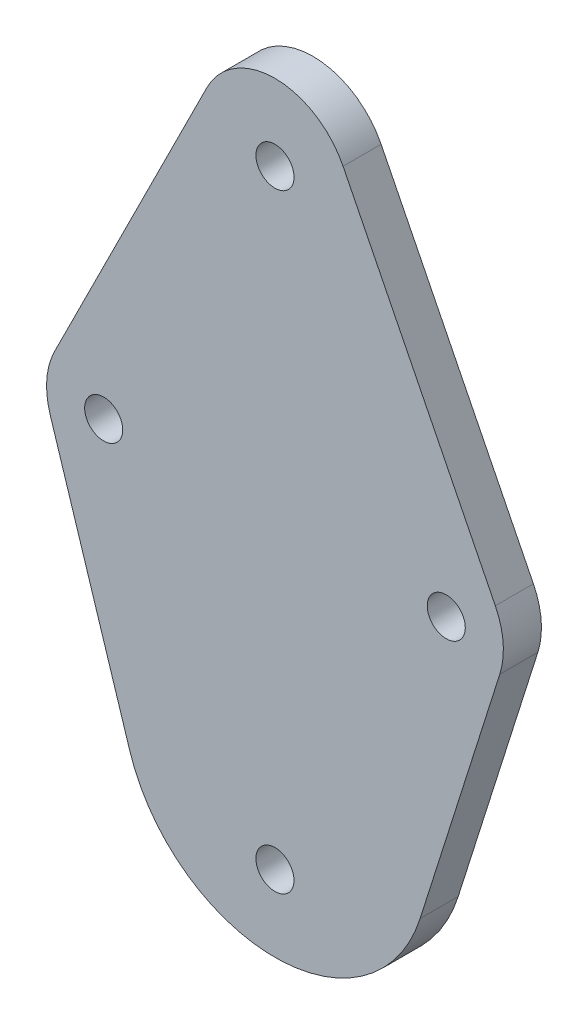
SolidWorks part; units mm, degrees
ref_plane "Front Plane" through (0, 0, 0) normal (0, 0, 1) x (1, 0, 0)
ref_plane "Top Plane" through (0, 0, 0) normal (0, 1, 0) x (1, 0, 0)
ref_plane "Right Plane" through (0, 0, 0) normal (1, 0, 0) x (0, 0, -1)
sketch "Sketch1" plane through (0, 0, 0) normal (0, 0, 1) x (1, 0, 0)
  line L0 (28.9443, 4.4721) -> (8.9443, 44.4721)
  line L1 (-8.9443, 44.4721) -> (-28.9443, 4.4721)
  line L2 (-29.5325, -3.0217) -> (-19.0651, -36.0434)
  line L3 (19.0651, -36.0434) -> (29.5325, -3.0217)
  arc A0 (8.9443, 44.4721) -> (-8.9443, 44.4721) centre (0, 40) ccw
  arc A1 (-19.0651, -36.0434) -> (19.0651, -36.0434) centre (0, -30) ccw
  arc A2 (28.9443, 4.4721) -> (29.5325, -3.0217) centre (20, 0) cw
  arc A3 (-28.9443, 4.4721) -> (-29.5325, -3.0217) centre (-20, 0) ccw
  point P12 (0, 0)
  point P14 (0, 0)
  point P15 (0, 0)
  point P16 (0, -8.3199)
  point P17 (9.0443, -23.4719)
  point P18 (11.9385, -26.2257)
  point P19 (0, 48.8586)
  point P20 (0, -11.8566)
  point P21 (-29.4559, 3.2535)
  dimension "D1" = 10
  dimension "D2" = 10
  dimension "D3" = 20
  dimension "D4" = 70
  dimension "D5" = 40
  dimension "D6" = 40
extrude "Boss-Extrude1" add sketch "Sketch1" along normal blind 5
sketch "Sketch2" plane through (0, 0, 5) normal (0, 0, 1) x (1, 0, 0)
  circle A0 centre (0, 40) radius 2.5
  circle A1 centre (0, -40) radius 2.5
  circle A2 centre (22.5, 0) radius 2.5
  circle A3 centre (-22.5, 0) radius 2.5
  point P8 (-22.5, 0)
  point P10 (0, 0)
  point P11 (0, 0)
  point P12 (0, 60)
  dimension "D1" = 5
  dimension "D2" = 45
  dimension "D3" = 22.5
  dimension "D4" = 80
  dimension "D5" = 40
extrude "Cut-Extrude1" cut sketch "Sketch2" against normal through all
